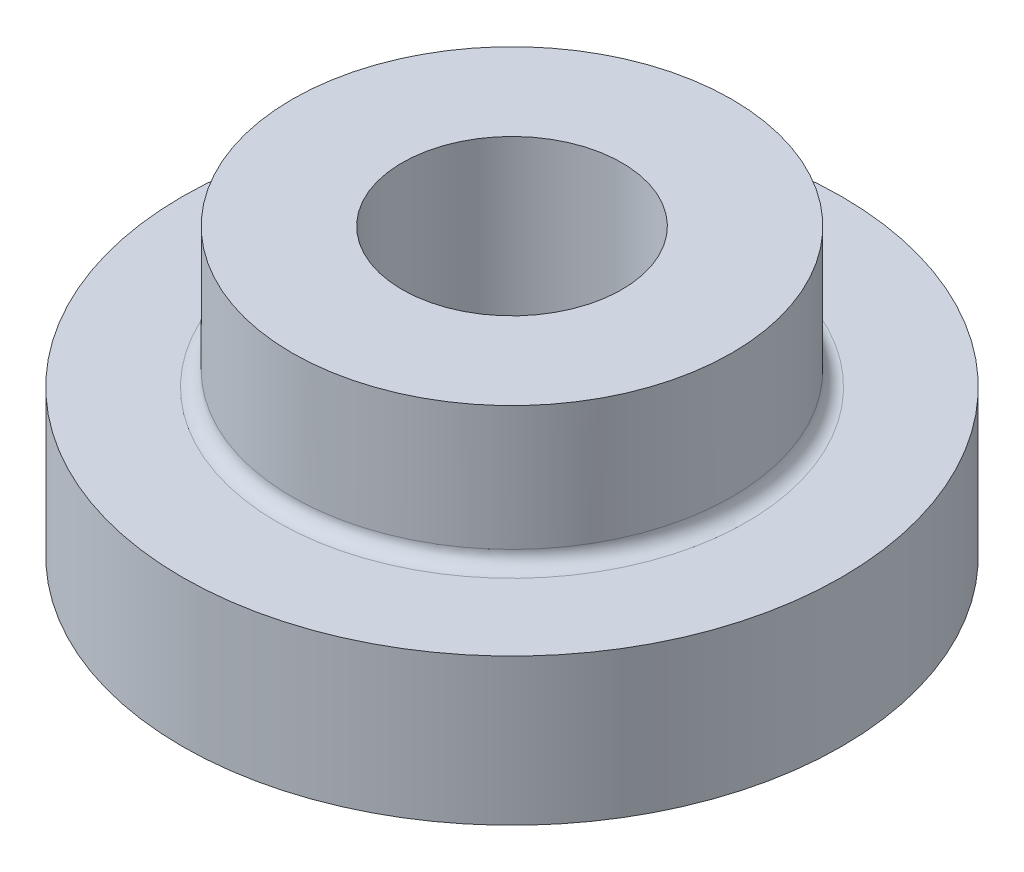
SolidWorks part; units mm, degrees
ref_plane "Front Plane" through (0, 0, 0) normal (0, 0, 1) x (1, 0, 0)
ref_plane "Top Plane" through (0, 0, 0) normal (0, 1, 0) x (1, 0, 0)
ref_plane "Right Plane" through (0, 0, 0) normal (1, 0, 0) x (0, 0, -1)
sketch "Sketch1" plane through (0, 0, 0) normal (0, 1, 0) x (1, 0, 0)
  circle A0 centre (0, 0) radius 3
  dimension "D1" = 6
extrude "Boss-Extrude1" add sketch "Sketch1" along normal blind 2.3
shell "Shell1" thickness 1.5
sketch "Sketch2" plane through (0, 0, 0) normal (0, -1, 0) x (1, 0, 0)
  circle A0 centre (0, 0) radius 3 construction
  circle A1 centre (0, 0) radius 3
  circle A2 centre (0, 0) radius 4.5
  dimension "D1" = 1.5
extrude "Boss-Extrude2" add sketch "Sketch2" along normal blind 1.6 and the other way blind 0.4
fillet "Fillet4" radius 0.2 2 edges at (0, 0, 3) (0, 0.4, -3)
